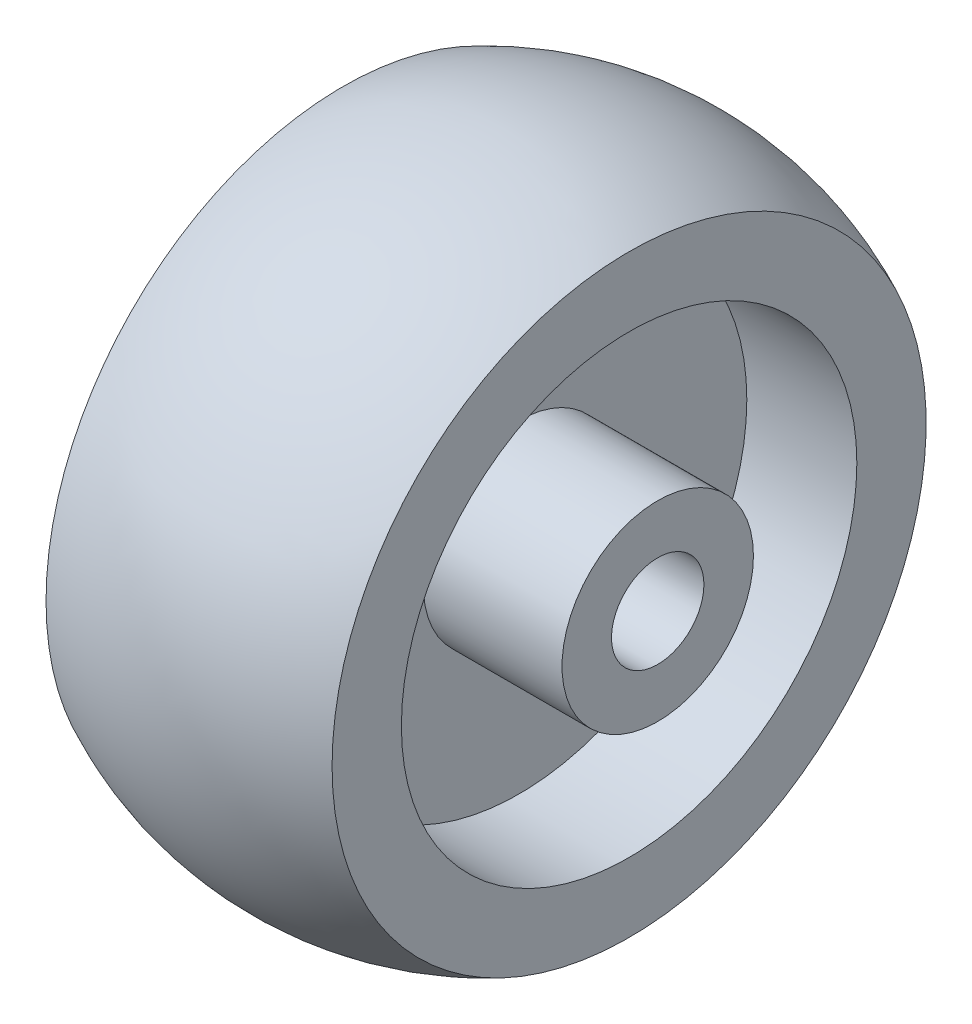
SolidWorks part; units mm, degrees
material "ABS PC"
ref_plane "Front Plane" through (0, 0, 0) normal (0, 0, 1) x (1, 0, 0)
ref_plane "Top Plane" through (0, 0, 0) normal (0, 1, 0) x (1, 0, 0)
ref_plane "Right Plane" through (0, 0, 0) normal (1, 0, 0) x (0, 0, -1)
sketch "Sketch5" plane through (0, 0, 0) normal (0, 0, 1) x (1, 0, 0)
  line L0 (0, 0) -> (6.5, 0) construction
  line L1 (6.5, 0) -> (6.5, 13.5)
  line L2 (0, 0) -> (0, 19.6596) construction
  line L3 (-6.5, 0) -> (-6.5, 13.5)
  line L4 (-6.5, 0) -> (6.5, 0)
  arc A0 (-6.5, 13.5) -> (6.5, 13.5) centre (0, -0.0185) cw
  dimension "D3" = 15
  dimension "D1" = 13.5
  dimension "D2" = 6.5
revolve "Revolve1" add sketch "Sketch5" angle 360 about L4
sketch "Sketch6" plane through (6.5, 0, 0) normal (1, 0, 0) x (0, 0, -1)
  circle A0 centre (0, 0) radius 10.35
  dimension "D1" = 20.7
extrude "Cut-Extrude1" cut sketch "Sketch6" against normal blind 5
sketch "Sketch7" plane through (1.5, 0, 0) normal (1, 0, 0) x (0, 0, -1)
  circle A0 centre (0, 0) radius 4.35
  circle A1 centre (0, 0) radius 2.1
  dimension "D1" = 8.7
  dimension "D2" = 4.2
extrude "Boss-Extrude3" add sketch "Sketch7" along normal blind 6.3
mirror "Mirror2" about plane through (0, 0, 0) normal (1, 0, 0) of "Cut-Extrude1", "Boss-Extrude3"
